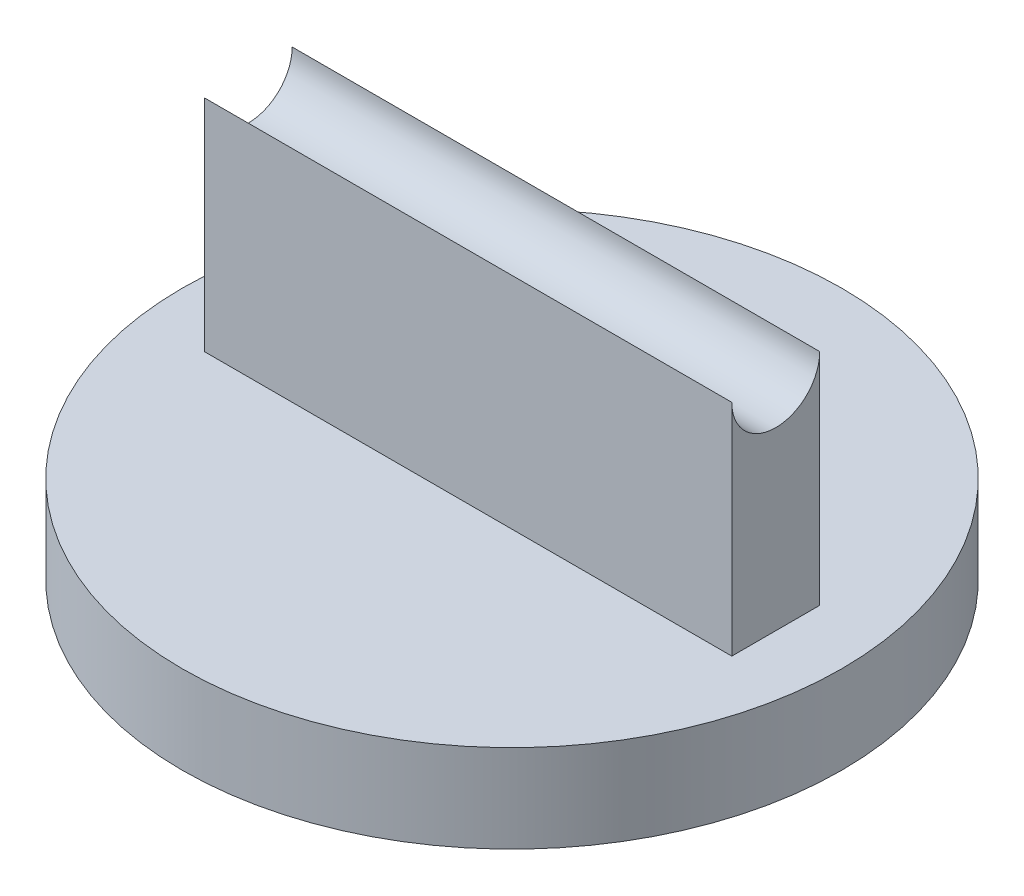
SolidWorks part; units mm, degrees
ref_plane "Ebene vorne" through (0, 0, 0) normal (0, 0, 1) x (1, 0, 0)
ref_plane "Ebene oben" through (0, 0, 0) normal (0, 1, 0) x (1, 0, 0)
ref_plane "Ebene rechts" through (0, 0, 0) normal (1, 0, 0) x (0, 0, -1)
sketch "Skizze1" plane through (0, 0, 0) normal (0, 1, 0) x (1, 0, 0)
  circle A0 centre (0, 0) radius 75
  dimension "D1" = 150
extrude "Aufsatz-Linear austragen1" add sketch "Skizze1" along normal blind 20
sketch "Skizze2" plane through (0, 20, 0) normal (0, 1, 0) x (1, 0, 0)
  line L1 (-60, 10) -> (60, 10)
  line L2 (-60, 10) -> (-60, -10)
  line L3 (-60, -10) -> (60, -10)
  line L4 (60, 10) -> (60, -10)
  line L5 (-60, 10) -> (60, -10) construction
  line L6 (-60, -10) -> (60, 10) construction
  point P0 (0, 0)
  dimension "D1" = 120
  dimension "D2" = 20
extrude "Aufsatz-Linear austragen2" add sketch "Skizze2" along normal blind 50
sketch "Skizze4" plane through (-60, 0, 0) normal (-1, 0, 0) x (0, 0, 1)
  line L0 (-10, 70) -> (10, 70) construction
  circle A0 centre (0, 70) radius 10
extrude "Schnitt-Linear austragen2" cut sketch "Skizze4" against normal blind 122
